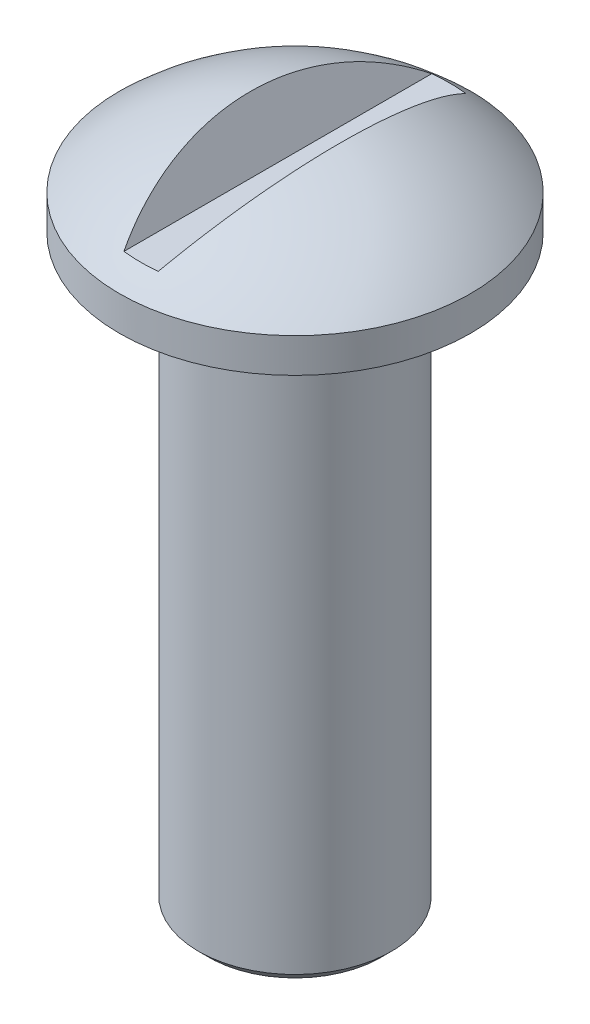
SolidWorks part; units mm, degrees
ref_plane "Front Plane" through (0, 0, 0) normal (0, 0, 1) x (1, 0, 0)
ref_plane "Top Plane" through (0, 0, 0) normal (0, 1, 0) x (1, 0, 0)
ref_plane "Right Plane" through (0, 0, 0) normal (1, 0, 0) x (0, 0, -1)
sketch "Sketch2" plane through (0, 0, 0) normal (0, 0, 1) x (1, 0, 0)
  line L0 (0, -6.5348) -> (0, 69.0904) construction
  line L2 (-6.35, 0) -> (-7.112, 0.762)
  line L3 (-7.112, 0.762) -> (-7.112, 43.18)
  line L4 (-7.112, 43.18) -> (-12.9515, 43.18)
  line L5 (-12.9515, 43.18) -> (-12.9515, 45.72)
  line L13 (0, 50.8) -> (0, 66.4309) construction
  line L15 (0, 0) -> (0, 50.8)
  line L16 (-6.35, 0) -> (0, 0)
  line L18 (15.8915, 46.99) -> (-15.8915, 46.99) construction
  arc A0 (-12.9515, 45.72) -> (0, 50.8) centre (0, 31.75) cw
  point P13 (0, 46.99)
  point P14 (0, 0)
  dimension "D2" = 6.35
  dimension "D8" = 3.81
  dimension "D1" = 19.05
  dimension "D3" = 45
  dimension "D4" = 43.18
  dimension "D5" = 50.8
  dimension "D6" = 2.54
  dimension "D7" = 0.762
revolve "Revolve3" add sketch "Sketch2" angle 360 about L0
ref_plane "Plane1" through (0, 46.99, 0) normal (0, 1, 0) x (1, 0, 0)
sketch "Sketch4" plane through (0, 46.99, 0) normal (0, 1, 0) x (1, 0, 0)
  line L0 (0, -15.326) -> (0, 14.0522) construction
  line L2 (-1.27, 13.5856) -> (1.27, 13.5856)
  line L3 (-1.27, 13.5856) -> (-1.27, -13.5856)
  line L4 (-1.27, -13.5856) -> (1.27, -13.5856)
  line L5 (1.27, 13.5856) -> (1.27, -13.5856)
  line L6 (-1.27, 13.5856) -> (1.27, -13.5856) construction
  line L7 (-1.27, -13.5856) -> (1.27, 13.5856) construction
  point P3 (0, 0)
  dimension "D1" = 2.54
extrude "Cut-Extrude1" cut sketch "Sketch4" along normal through all draft 30
